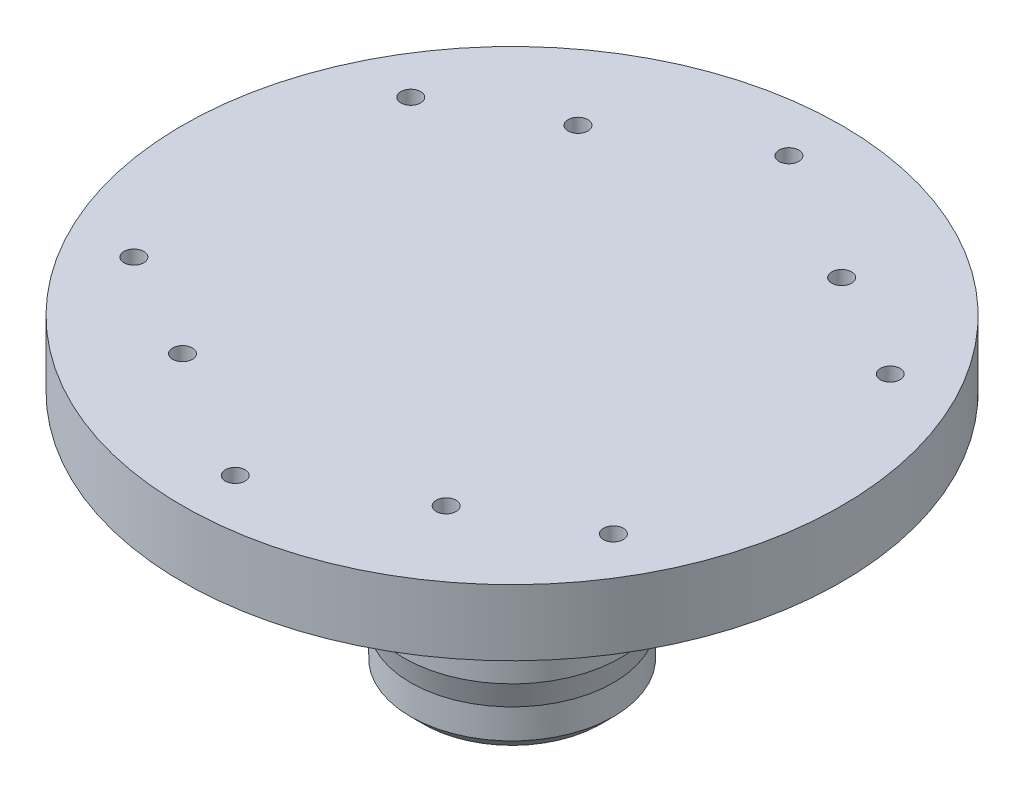
SolidWorks part; units mm, degrees
ref_plane "Front Plane" through (0, 0, 0) normal (0, 0, 1) x (1, 0, 0)
ref_plane "Top Plane" through (0, 0, 0) normal (0, 1, 0) x (1, 0, 0)
ref_plane "Right Plane" through (0, 0, 0) normal (1, 0, 0) x (0, 0, -1)
sketch "Sketch1" plane through (0, 0, 0) normal (0, 0, 1) x (1, 0, 0)
  line L0 (10.2, 18.5) -> (10.2, 14.5)
  line L6 (0, 0) -> (8.2, 0)
  line L7 (10.2, 14.5) -> (8.2, 14.5)
  line L8 (8.2, 14.5) -> (8.2, 0)
  line L12 (0, 0) -> (0, 23.5)
  line L14 (10.2, 18.5) -> (25, 18.5)
  line L15 (25, 18.5) -> (25, 23.5)
  line L16 (25, 23.5) -> (0, 23.5)
  dimension "D1" = 25
  dimension "D2" = 8.2
  dimension "D3" = 2
  dimension "D4" = 4
  dimension "D5" = 14.5
  dimension "D9" = 5
revolve "Revolve1" add sketch "Sketch1" angle 360 about L12
sketch "Sketch5" plane through (0, 23.5, 0) normal (0, 1, 0) x (1, 0, 0)
  line L0 (0, 0) -> (0, 21) construction
  circle A0 centre (0, 21) radius 0.75
  dimension "D1" = 1.5
  dimension "D2" = 21
extrude "Cut-Extrude1" cut sketch "Sketch5" against normal through all
pattern_circular "CirPattern2" count 6 over 360 about axis through (0, 0, 0) along (0, 1, 0) of "Cut-Extrude1"
sketch "Sketch6" plane through (0, 23.5, 0) normal (0, 1, 0) x (1, 0, 0)
  line L1 (-10, 15) -> (10, 15) construction
  line L2 (-10, 15) -> (-10, -15) construction
  line L3 (-10, -15) -> (10, -15) construction
  line L4 (10, 15) -> (10, -15) construction
  line L5 (0, -15) -> (0, 15) construction
  line L6 (-10, 0) -> (10, 0) construction
  circle A0 centre (-10, 15) radius 0.75
  circle A1 centre (10, 15) radius 0.75
  circle A2 centre (-10, -15) radius 0.75
  circle A3 centre (10, -15) radius 0.75
  point P124 (0, 0)
  dimension "D3" = 1.5
  dimension "D4" = 1.5
  dimension "D5" = 1.5
  dimension "D6" = 1.5
  dimension "D1" = 30
  dimension "D2" = 20
extrude "Cut-Extrude2" cut sketch "Sketch6" against normal through all
sketch "Sketch7" plane through (0, 0, 0) normal (0, -1, 0) x (1, 0, 0)
  circle A0 centre (0, 0) radius 2.6
  dimension "D1" = 5.2
extrude "Cut-Extrude3" cut sketch "Sketch7" against normal blind 4
sketch "Sketch8" plane through (0, 0, 0) normal (0, 0, 1) x (1, 0, 0)
  line L0 (-8.2, 5.1) -> (-7.7, 3.234)
  line L1 (-8.2, 14.5) -> (-8.2, 0) construction
  line L2 (-7.7, 3.234) -> (-7.7, 0)
  line L3 (-8.2, 0) -> (8.2, 0) construction
  line L4 (-7.7, 0) -> (-8.2, 0)
  line L5 (-8.2, 0) -> (-8.2, 5.1)
  dimension "D1" = 5.1
  dimension "D2" = 0.5
  dimension "D3" = 15
ref_axis "Axis1" through (0, 14.5, 0) along (0, -1, 0)
revolve "Cut-Revolve1" cut sketch "Sketch8" angle 360 about axis through (0, 14.5, 0) along (0, -1, 0)
chamfer "Chamfer1" distance 0.5 angle 45 1 edges at (0, 0, -2.6)
chamfer "Chamfer2" distance 1 angle 45 1 edges at (0, 0, 7.7)
equation "\"D4@Sketch6\"=\"D3@Sketch6\""
equation "\"D5@Sketch6\"=\"D3@Sketch6\""
equation "\"D6@Sketch6\"=\"D3@Sketch6\""
